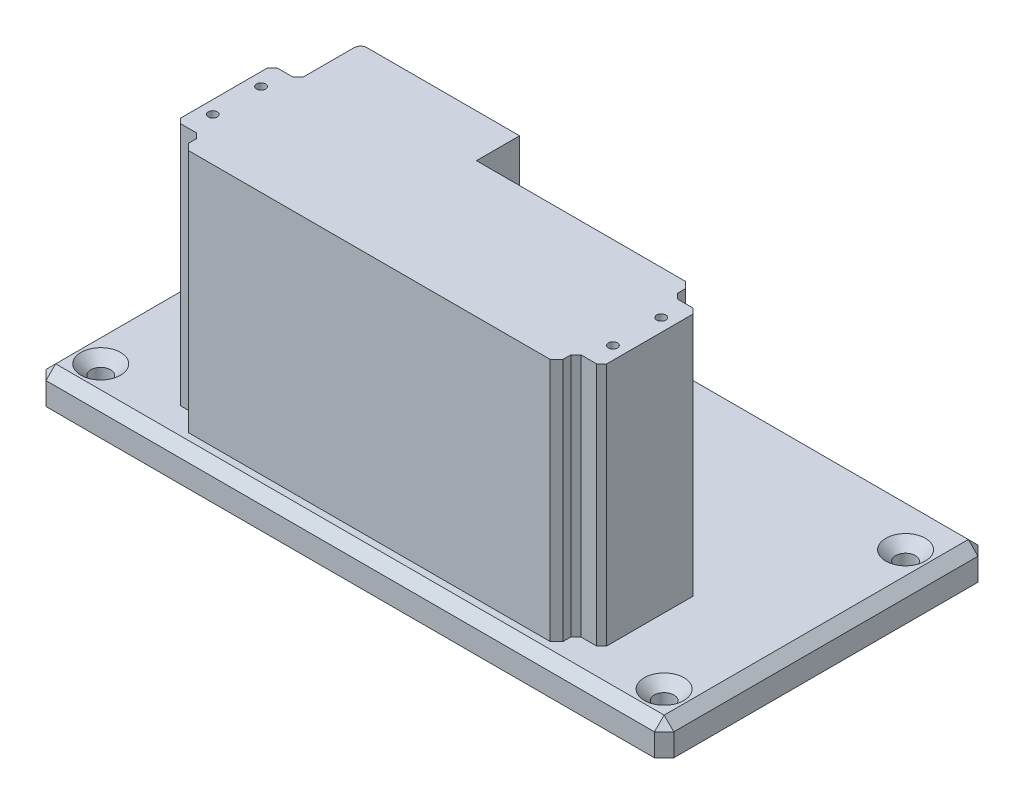
SolidWorks part; units mm, degrees
ref_plane "Front Plane" through (0, 0, 0) normal (0, 0, 1) x (1, 0, 0)
ref_plane "Top Plane" through (0, 0, 0) normal (0, 1, 0) x (1, 0, 0)
ref_plane "Right Plane" through (0, 0, 0) normal (1, 0, 0) x (0, 0, -1)
sketch "Sketch1" plane through (0, 0, 0) normal (0, 1, 0) x (1, 0, 0)
  line L0 (0, 47.5) -> (195, 47.5) construction
  line L1 (0, 0) -> (195, 0)
  line L2 (0, 0) -> (0, 95)
  line L3 (0, 95) -> (195, 95) construction
  line L4 (195, 0) -> (195, 95)
  line L5 (97.5, 95) -> (97.5, 0) construction
  line L7 (10, 85) -> (185, 85) construction
  line L8 (10, 85) -> (10, 10) construction
  line L9 (10, 10) -> (185, 10) construction
  line L10 (185, 85) -> (185, 10) construction
  line L11 (0, 95) -> (195, 95) construction
  line L12 (0, 95) -> (0, 100.5)
  line L13 (0, 100.5) -> (195, 100.5)
  line L14 (195, 95) -> (195, 100.5)
  circle A0 centre (10, 85) radius 3.05
  circle A1 centre (185, 85) radius 3.05
  circle A2 centre (185, 10) radius 3.05
  circle A3 centre (10, 10) radius 3.05
  dimension "D5" = 6.1
  dimension "D1" = 195
  dimension "D2" = 95
  dimension "D3" = 75
  dimension "D4" = 175
  dimension "D6" = 5.5
extrude "Boss-Extrude1" add sketch "Sketch1" along normal blind 10
sketch "Sketch2" plane through (0, 10, 0) normal (0, 1, 0) x (1, 0, 0)
  line L0 (42.2, 60.5) -> (89.6, 60.5)
  line L1 (40.2, 60.5) -> (40.2, 5.1) construction
  line L2 (40.2, 5.1) -> (156.5, 5.1)
  line L3 (156.5, 5.1) -> (156.5, 47.1) construction
  line L4 (89.6, 60.5) -> (89.6, 47.1)
  line L5 (89.6, 47.1) -> (156.5, 47.1)
  line L6 (156.5, 26.1) -> (40.2, 26.1) construction
  line L7 (156.5, 41.1) -> (164.5, 41.1)
  line L8 (156.5, 41.1) -> (156.5, 11.1) construction
  line L9 (156.5, 11.1) -> (164.5, 11.1)
  line L10 (164.5, 41.1) -> (164.5, 11.1)
  line L11 (98.35, 5.1) -> (98.35, 47.1) construction
  line L12 (40.2, 11.1) -> (32.2, 11.1)
  line L13 (32.2, 41.1) -> (32.2, 11.1)
  line L14 (40.2, 41.1) -> (32.2, 41.1)
  line L15 (40.2, 41.1) -> (40.2, 11.1) construction
  line L16 (40.2, 58.5) -> (40.2, 41.1)
  line L17 (40.2, 11.1) -> (40.2, 5.1)
  line L18 (156.5, 11.1) -> (156.5, 5.1)
  line L19 (156.5, 47.1) -> (156.5, 41.1)
  line L20 (80.2, 5.1) -> (80.2, 60.5) construction
  line L22 (60.2, 5.1) -> (60.2, 60.5) construction
  line L24 (195, 100.5) -> (0, 100.5) construction
  arc A0 (42.2, 60.5) -> (40.2, 58.5) centre (42.2, 58.5) ccw
  circle A1 centre (10, 85) radius 3.05 construction
  dimension "D6" = 2
  dimension "D11" = 42
  dimension "D1" = 116.3
  dimension "D2" = 8
  dimension "D3" = 49.4
  dimension "D4" = 13.4
  dimension "D5" = 30
  dimension "D7" = 40
  dimension "D8" = 20
  dimension "D9" = 50.2
  dimension "D10" = 40
extrude "Boss-Extrude2" add sketch "Sketch2" along normal blind 75.9 contours L16 L14 L13 L12 L17 L2 L18 L9 L10 L7 L19 L5 L4 L0 A0
sketch "Sketch3" plane through (0, 85.9, 0) normal (0, 1, 0) x (1, 0, 0)
  line L0 (98.35, 5.1) -> (98.35, 47.1) construction
  line L1 (32.2, 41.1) -> (40.2, 41.1) construction
  line L2 (32.2, 41.1) -> (32.2, 11.1) construction
  line L3 (32.2, 11.1) -> (40.2, 11.1) construction
  line L4 (40.2, 41.1) -> (40.2, 11.1) construction
  line L5 (40.2, 5.1) -> (156.5, 5.1) construction
  line L6 (89.6, 47.1) -> (156.5, 47.1) construction
  line L7 (36.2, 41.1) -> (36.2, 11.1) construction
  line L8 (32.2, 26.1) -> (40.2, 26.1) construction
  circle A0 centre (36.2, 33.6) radius 1.4
  circle A1 centre (36.2, 18.6) radius 1.4
  circle A2 centre (160.5, 18.6) radius 1.4
  circle A3 centre (160.5, 33.6) radius 1.4
  dimension "D1" = 2.8
  dimension "D2" = 7.5
extrude "Cut-Extrude1" cut sketch "Sketch3" against normal blind 6
chamfer "Chamfer1" distance 1.55 angle 45 8 edges at (40.2, 47.95, -11.1) (32.2, 47.95, -11.1) (32.2, 47.95, -41.1) (40.2, 47.95, -41.1) (164.5, 47.95, -11.1) (156.5, 47.95, -11.1) (156.5, 47.95, -41.1) (164.5, 47.95, -41.1)
chamfer "Chamfer2" distance 2 angle 45 3 edges at (40.2, 47.95, -5.1) (156.5, 47.95, -47.1) (156.5, 47.95, -5.1)
chamfer "Chamfer3" distance 3.1 angle 45 4 edges at (185, 10, -6.95) (185, 10, -88.05) (10, 10, -13.05) (10, 10, -81.95)
chamfer "Chamfer4" distance 3 angle 45 8 edges at (195, 5, -100.5) (195, 10, -50.25) (195, 5, 0) (0, 5, -100.5) (97.5, 10, -100.5) (0, 5, 0) (97.5, 10, 0) (0, 10, -50.25)
